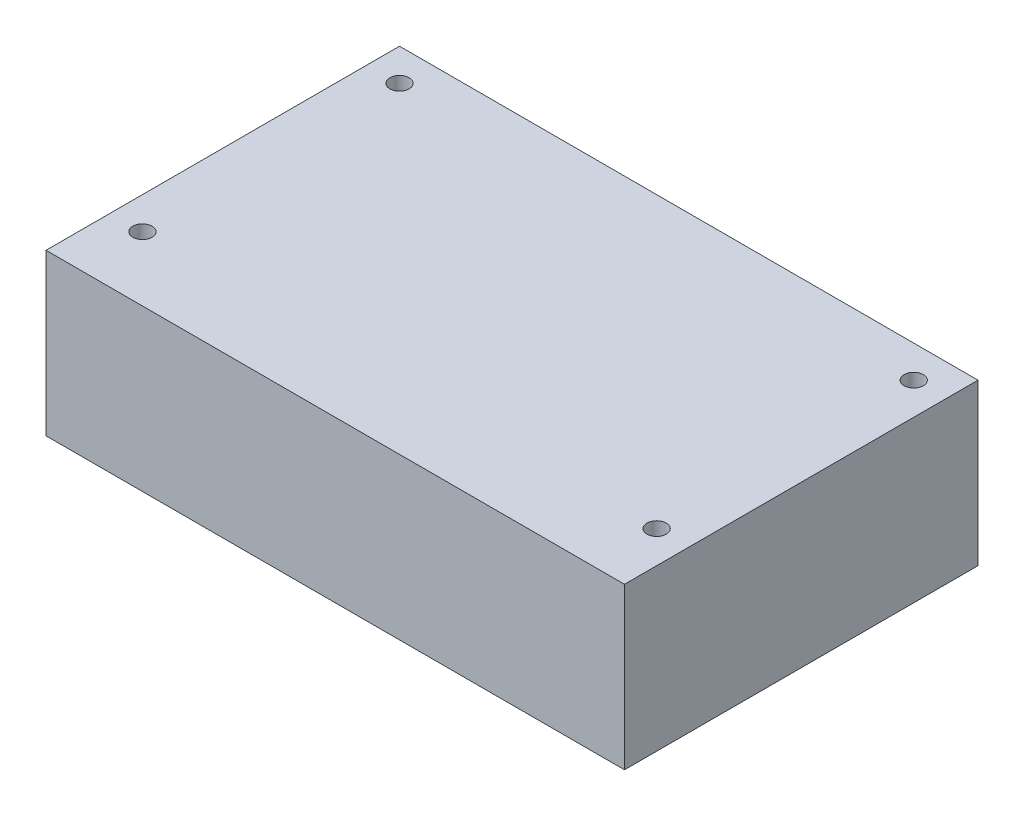
SolidWorks part; units mm, degrees
ref_plane "Front Plane" through (0, 0, 0) normal (0, 0, 1) x (1, 0, 0)
ref_plane "Top Plane" through (0, 0, 0) normal (0, 1, 0) x (1, 0, 0)
ref_plane "Right Plane" through (0, 0, 0) normal (1, 0, 0) x (0, 0, -1)
sketch "Sketch1" plane through (0, 0, 0) normal (0, 1, 0) x (1, 0, 0)
  line L1 (-45, -27.5) -> (45, -27.5)
  line L2 (-45, -27.5) -> (-45, 27.5)
  line L3 (-45, 27.5) -> (45, 27.5)
  line L4 (45, -27.5) -> (45, 27.5)
  line L5 (-45, -27.5) -> (45, 27.5) construction
  line L6 (-45, 27.5) -> (45, -27.5) construction
  circle A0 centre (-40, 22.5) radius 1.5
  circle A1 centre (40, 22.5) radius 1.5
  circle A2 centre (40, -17.5) radius 1.5
  circle A3 centre (-40, -17.5) radius 1.5
  point P0 (0, 0)
  dimension "D3" = 3
  dimension "D4" = 3
  dimension "D5" = 3
  dimension "D6" = 3
  dimension "D1" = 90
  dimension "D2" = 55
  dimension "D7" = 5
  dimension "D8" = 5
  dimension "D9" = 5
  dimension "D10" = 5
  dimension "D11" = 10
  dimension "D12" = 5
  dimension "D13" = 10
  dimension "D14" = 5
extrude "Boss-Extrude1" add sketch "Sketch1" along normal blind 25
